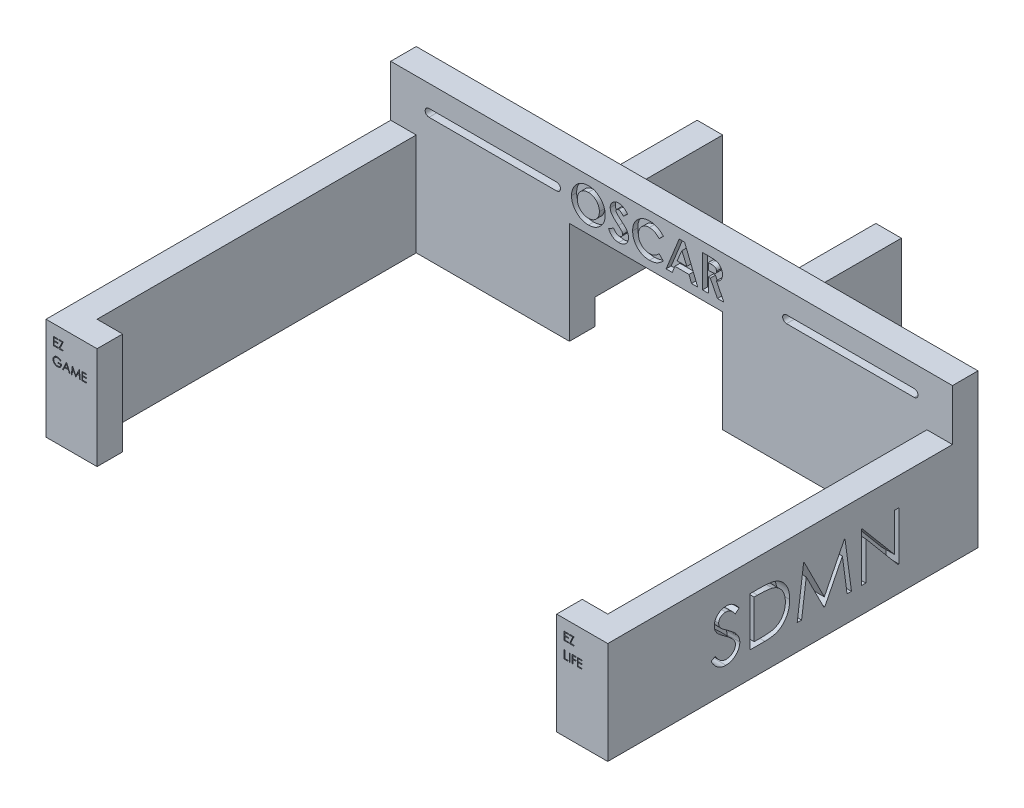
SolidWorks part; units mm, degrees
ref_plane "Front Plane" through (0, 0, 0) normal (0, 0, 1) x (1, 0, 0)
ref_plane "Top Plane" through (0, 0, 0) normal (0, 1, 0) x (1, 0, 0)
ref_plane "Right Plane" through (0, 0, 0) normal (1, 0, 0) x (0, 0, -1)
sketch "Sketch2" plane through (0, 0, 0) normal (0, 0, 1) x (1, 0, 0)
  line L0 (0, -55) -> (0, 55) construction
  line L1 (-110, 16.7568) -> (110, 16.7568)
  line L2 (-110, 16.7568) -> (-110, 36.7568)
  line L3 (-110, 36.7568) -> (110, 36.7568)
  line L4 (110, 16.7568) -> (110, 36.7568)
  line L5 (-110, 16.7568) -> (110, 36.7568) construction
  line L6 (-110, 36.7568) -> (110, 16.7568) construction
  line L8 (-110, 16.7568) -> (-40, 16.7568)
  line L9 (-110, 16.7568) -> (-110, -23.2432)
  line L10 (-110, -23.2432) -> (-40, -23.2432)
  line L11 (-40, 16.7568) -> (-40, -23.2432)
  line L13 (110, 16.7568) -> (40, 16.7568)
  line L15 (-95, 25.2568) -> (-45, 25.2568)
  line L16 (110, 16.7568) -> (20, 16.7568)
  line L17 (110, 16.7568) -> (110, -23.2432)
  line L18 (110, -23.2432) -> (20, -23.2432)
  line L19 (20, 16.7568) -> (20, -23.2432)
  line L20 (-95, 28.2568) -> (-45, 28.2568)
  line L21 (45, 28.2568) -> (95, 28.2568)
  line L22 (95, 25.2568) -> (45, 25.2568)
  circle A0 centre (-45, 26.7568) radius 1.5
  circle A1 centre (-95, 26.7568) radius 1.5
  circle A2 centre (95, 26.7568) radius 1.5
  circle A3 centre (45, 26.7568) radius 1.5
  point P0 (0, 26.7568)
  dimension "D5" = 3
  dimension "D6" = 3
  dimension "D1" = 220
  dimension "D2" = 20
  dimension "D3" = 40
  dimension "D4" = 70
  dimension "D7" = 10
  dimension "D8" = 10
  dimension "D9" = 15
  dimension "D10" = 50
  dimension "D11" = 90
extrude "Boss-Extrude1" add sketch "Sketch2" along normal blind 10
sketch "Sketch3" plane through (0, 0, 10) normal (0, 0, 1) x (1, 0, 0)
  line L0 (0, -55) -> (0, 55) construction
  line L1 (-110, -23.2432) -> (-100, -23.2432)
  line L2 (-110, -23.2432) -> (-110, 16.7568)
  line L3 (-110, 16.7568) -> (-100, 16.7568)
  line L4 (-100, -23.2432) -> (-100, 16.7568)
  line L5 (110, 16.7568) -> (100, 16.7568)
  line L6 (100, -23.2432) -> (100, 16.7568)
  line L7 (110, -23.2432) -> (100, -23.2432)
  line L8 (110, -23.2432) -> (110, 16.7568)
  dimension "D1" = 40
  dimension "D2" = 10
extrude "Boss-Extrude2" add sketch "Sketch3" along normal blind 135
sketch "Sketch4" plane through (-100, 0, 0) normal (1, 0, 0) x (0, 0, -1)
  line L0 (-145, 16.7568) -> (-10, 16.7568) construction
  line L1 (-145, -23.2432) -> (-135, -23.2432)
  line L2 (-145, -23.2432) -> (-145, 16.7568)
  line L3 (-145, 16.7568) -> (-135, 16.7568)
  line L4 (-135, -23.2432) -> (-135, 16.7568)
  dimension "D1" = 10
extrude "Boss-Extrude3" add sketch "Sketch4" along normal blind 10
mirror "Mirror1" about plane through (0, 0, 0) normal (1, 0, 0) of "Boss-Extrude3"
sketch "Sketch5" plane through (0, 0, 0) normal (0, 0, -1) x (-1, 0, 0)
  line L1 (-20, 16.7568) -> (-30, 16.7568)
  line L2 (-20, 16.7568) -> (-20, -13.2432)
  line L3 (-20, -13.2432) -> (-30, -13.2432)
  line L4 (-30, 16.7568) -> (-30, -13.2432)
  line L10 (40, 16.7568) -> (50, 16.7568)
  line L11 (40, 16.7568) -> (40, -13.2432)
  line L12 (40, -13.2432) -> (50, -13.2432)
  line L13 (50, 16.7568) -> (50, -13.2432)
  dimension "D1" = 10
  dimension "D2" = 30
  dimension "D3" = 10
  dimension "D4" = 30
extrude "Boss-Extrude4" add sketch "Sketch5" along normal blind 50
sketch "Sketch6" plane through (-110, 0, 0) normal (-1, 0, 0) x (0, 0, 1)
  line L0 (145, 16.7568) -> (10, 16.7568) construction
  line L1 (28.8985, -15.7432) -> (30.8985, -15.7432)
  line L2 (28.8985, -15.7432) -> (28.8985, 9.2568)
  line L3 (28.8985, 9.2568) -> (30.8985, 9.2568)
  line L4 (30.8985, -15.7432) -> (30.8985, 9.2568)
  line L5 (30.8985, 9.2568) -> (45.8985, -12.7432)
  line L6 (45.8985, -15.7432) -> (47.8985, -15.7432)
  line L7 (45.8985, -15.7432) -> (45.8985, 9.2568)
  line L8 (45.8985, 9.2568) -> (47.8985, 9.2568)
  line L9 (47.8985, -15.7432) -> (47.8985, 9.2568)
  line L10 (30.8985, 6.2568) -> (45.8985, -15.7432)
  line L11 (45.8985, -15.7432) -> (45.8985, -12.7432)
  line L12 (30.8985, 6.2568) -> (30.8985, 9.2568)
  line L14 (92.8985, 9.2568) -> (94.8985, 9.2568)
  line L15 (92.8985, 9.2568) -> (92.8985, -15.7432)
  line L16 (92.8985, -15.7432) -> (94.8985, -15.7432)
  line L17 (94.8985, 9.2568) -> (94.8985, -15.7432)
  line L18 (92.8985, -15.7432) -> (107.8985, -15.7432)
  line L19 (92.8985, -15.7432) -> (92.8985, -13.7432)
  line L20 (92.8985, -13.7432) -> (107.8985, -13.7432)
  line L21 (107.8985, -15.7432) -> (107.8985, -13.7432)
  circle A0 centre (65.3985, -3.2432) radius 12.5
  circle A1 centre (65.3985, -3.2432) radius 10.5
  dimension "D8" = 25
  dimension "D11" = 21
  dimension "D1" = 2
  dimension "D2" = 25
  dimension "D3" = 7.5
  dimension "D4" = 2
  dimension "D5" = 15
  dimension "D6" = 3
  dimension "D7" = 3
  dimension "D9" = 20
  dimension "D10" = 17.5
  dimension "D12" = 2
  dimension "D13" = 45
  dimension "D14" = 2
  dimension "D15" = 15
extrude "Cut-Extrude1" cut sketch "Sketch6" against normal blind 5 contours L1 L4 L3 L2 | L4 L10 L7 L5 | A0 A1 | L18 L21 L20 L17
sketch "Sketch8" plane through (0, 0, 10) normal (0, 0, 1) x (1, 0, 0)
  line L0 (-110, 36.7568) -> (110, 36.7568) construction
  line L4 (-110, 36.7568) -> (-110, 16.7568) construction
  text T0 "<b>OSCAR</b>" font "Century Gothic" height in points 48
  dimension "D1" = 16.5
  dimension "D2" = 70
extrude "Cut-Extrude2" cut sketch "Sketch8" against normal blind 2
sketch "Sketch9" plane through (110, 0, 0) normal (1, 0, 0) x (0, 0, -1)
  line L0 (-145, -23.2432) -> (-145, 16.7568) construction
  line L1 (-145, 16.7568) -> (-10, 16.7568) construction
  text T0 "SDMN" font "Century Gothic" height in points 72
  dimension "D1" = 40
  dimension "D2" = 30
extrude "Cut-Extrude3" cut sketch "Sketch9" against normal blind 5
sketch "Sketch10" plane through (0, 0, 145) normal (0, 0, 1) x (1, 0, 0)
  line L0 (110, -23.2432) -> (110, 16.7568) construction
  line L1 (110, 16.7568) -> (90, 16.7568) construction
  line L2 (-90, 16.7568) -> (-90, -23.2432) construction
  line L3 (-90, 16.7568) -> (-110, 16.7568) construction
  text T0 "EZ\r\nGAME"
  text T1 "EZ\r\nLIFE"
  dimension "D1" = 17.5
  dimension "D2" = 7.5
  dimension "D3" = 17.5
  dimension "D4" = 7.5
extrude "Cut-Extrude4" cut sketch "Sketch10" against normal blind 1
